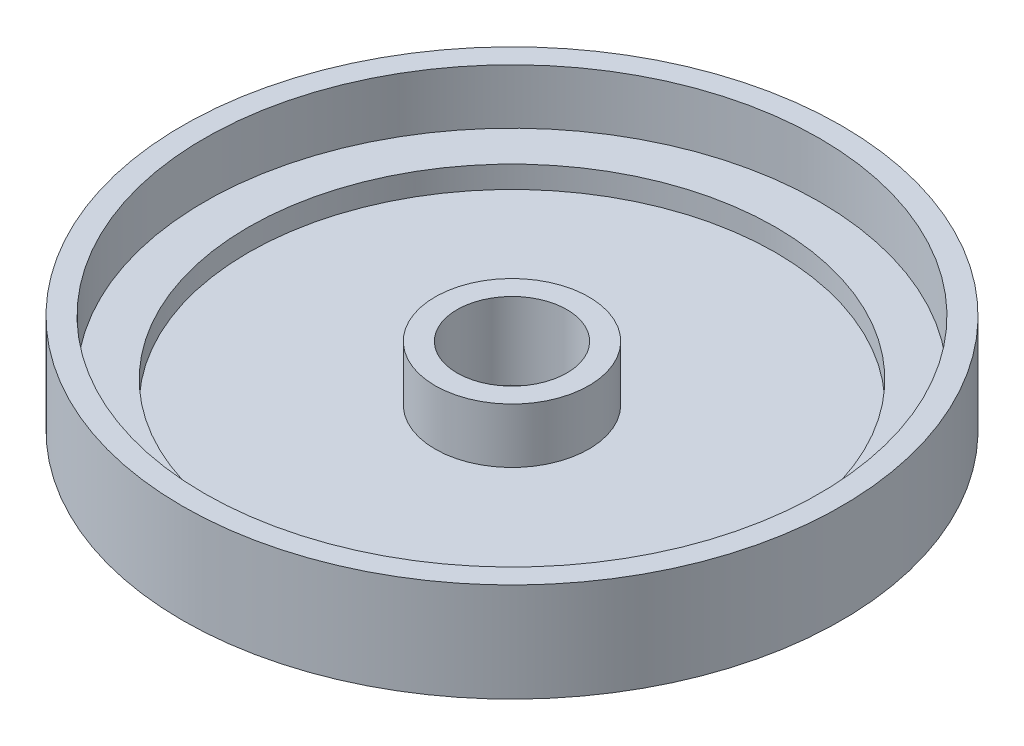
SolidWorks part; units mm, degrees
ref_plane "Front Plane" through (0, 0, 0) normal (0, 0, 1) x (1, 0, 0)
ref_plane "Top Plane" through (0, 0, 0) normal (0, 1, 0) x (1, 0, 0)
ref_plane "Right Plane" through (0, 0, 0) normal (1, 0, 0) x (0, 0, -1)
sketch "Sketch1" plane through (0, 0, 0) normal (0, 1, 0) x (1, 0, 0)
  circle A0 centre (0, 0) radius 6.35
  circle A1 centre (0, 0) radius 38.1
  dimension "D1" = 12.7
  dimension "D2" = 76.2
extrude "Boss-Extrude1" add sketch "Sketch1" along normal blind 2.54
sketch "Sketch2" plane through (0, 2.54, 0) normal (0, 1, 0) x (1, 0, 0)
  circle A0 centre (0, 0) radius 6.35
  circle A1 centre (0, 0) radius 8.89
  circle A2 centre (0, 0) radius 6.35 construction
  dimension "D1" = 2.54
extrude "Boss-Extrude2" add sketch "Sketch2" along normal blind 6.35
sketch "Sketch5" plane through (0, 2.54, 0) normal (0, 1, 0) x (1, 0, 0)
  circle A0 centre (0, 0) radius 38.1
  circle A1 centre (0, 0) radius 30.48
  circle A3 centre (0, 0) radius 38.1 construction
  dimension "D1" = 7.62
extrude "Boss-Extrude3" add sketch "Sketch5" along normal blind 2.54
sketch "Sketch6" plane through (0, 5.08, 0) normal (0, 1, 0) x (1, 0, 0)
  circle A0 centre (0, 0) radius 38.1
  circle A1 centre (0, 0) radius 35.56
  circle A2 centre (0, 0) radius 38.1 construction
  dimension "D1" = 2.54
extrude "Boss-Extrude4" add sketch "Sketch6" along normal blind 6.35
